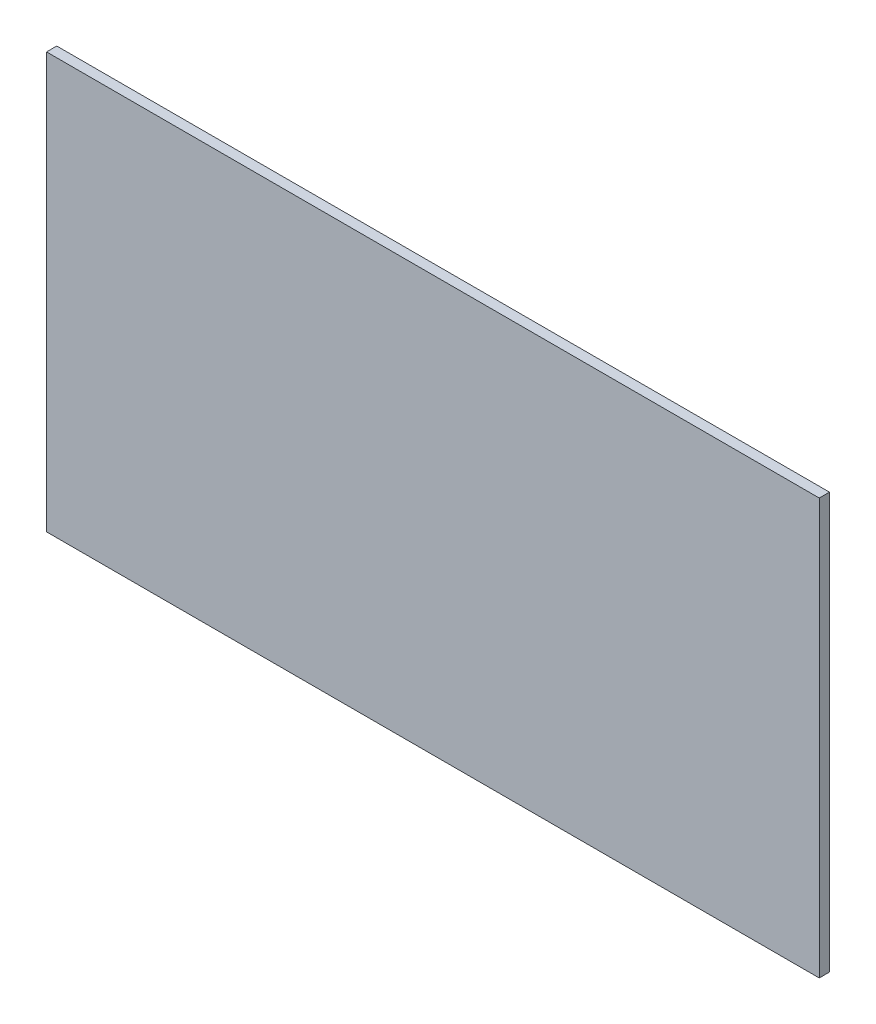
SolidWorks part; units mm, degrees
ref_plane "Plan de face" through (0, 0, 0) normal (0, 0, 1) x (1, 0, 0)
ref_plane "Plan de dessus" through (0, 0, 0) normal (0, 1, 0) x (1, 0, 0)
ref_plane "Plan de droite" through (0, 0, 0) normal (1, 0, 0) x (0, 0, -1)
sketch "Esquisse1" plane through (0, 0, 0) normal (0, 0, 1) x (1, 0, 0)
  line L1 (-151.5, -81.5) -> (151.5, -81.5)
  line L2 (-151.5, -81.5) -> (-151.5, 81.5)
  line L3 (-151.5, 81.5) -> (151.5, 81.5)
  line L4 (151.5, -81.5) -> (151.5, 81.5)
  line L5 (-151.5, -81.5) -> (151.5, 81.5) construction
  line L6 (-151.5, 81.5) -> (151.5, -81.5) construction
  point P0 (0, 0)
  dimension "D1" = 163
  dimension "D2" = 303
extrude "Boss.-Extru.1" add sketch "Esquisse1" along normal blind 4
